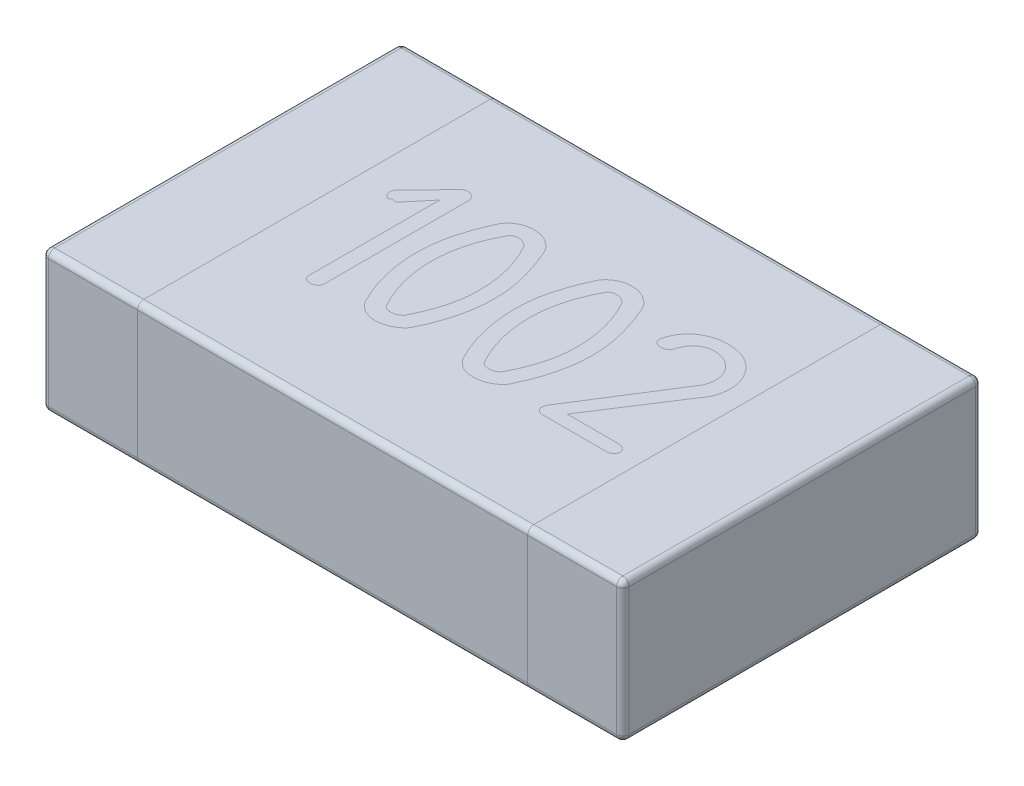
SolidWorks part; units mm, degrees
ref_plane "Front Plane" through (0, 0, 0) normal (0, 0, 1) x (1, 0, 0)
ref_plane "Top Plane" through (0, 0, 0) normal (0, 1, 0) x (1, 0, 0)
ref_plane "Right Plane" through (0, 0, 0) normal (1, 0, 0) x (0, 0, -1)
sketch "Sketch1" plane through (0, 0, 0) normal (0, 1, 0) x (1, 0, 0)
  line L1 (-0.91, -0.575) -> (0.91, -0.575)
  line L2 (-0.93, -0.555) -> (-0.93, 0.555)
  line L3 (-0.91, 0.575) -> (0.91, 0.575)
  line L4 (0.93, -0.555) -> (0.93, 0.555)
  line L5 (-0.93, -0.575) -> (0.93, 0.575) construction
  line L6 (-0.93, 0.575) -> (0.93, -0.575) construction
  arc A4 (-0.93, -0.555) -> (-0.91, -0.575) centre (-0.91, -0.555) ccw
  arc A5 (0.91, -0.575) -> (0.93, -0.555) centre (0.91, -0.555) ccw
  arc A6 (0.93, 0.555) -> (0.91, 0.575) centre (0.91, 0.555) ccw
  arc A7 (-0.91, 0.575) -> (-0.93, 0.555) centre (-0.91, 0.555) ccw
  point P0 (0, 0)
  dimension "D4" = 0.02
  dimension "D1" = 1.86
  dimension "D2" = 1.15
extrude "Boss-Extrude1" add sketch "Sketch1" along normal mid plane 0.45
sketch "Sketch3" plane through (0, 0.225, 0) normal (0, 1, 0) x (1, 0, 0)
  line L1 (-0.625, -0.575) -> (-0.625, 0.575)
  line L2 (0.625, -0.575) -> (0.625, 0.575)
  line L4 (0.91, 0.575) -> (-0.91, 0.575) construction
  point P4 (0, 0)
  point P8 (-0.625, 0)
  point P11 (0.625, 0)
  point P14 (0, 0)
  point P17 (0, -0.25)
  dimension "D1" = 1.25
sketch "Sketch4" plane through (0, 0, 0.575) normal (0, 0, 1) x (1, 0, 0)
  line L0 (-0.625, 0.225) -> (-0.625, -0.5946)
  line L1 (0.625, 0.225) -> (0.625, -0.5946)
sketch "Sketch5" plane through (0, 0, -0.575) normal (0, 0, -1) x (-1, 0, 0)
  line L0 (-0.625, 0.225) -> (-0.625, -0.5946) construction
  line L1 (-0.625, 0.225) -> (-0.625, -0.5946)
  line L2 (0.625, 0.225) -> (0.625, -0.5946) construction
  line L3 (0.625, 0.225) -> (0.625, -0.5946)
sketch "Sketch6" plane through (0, -0.225, 0) normal (0, -1, 0) x (1, 0, 0)
  line L0 (0.625, 0.575) -> (0.625, -0.575) construction
  line L1 (-0.625, 0.575) -> (-0.625, -0.575) construction
  line L2 (0.625, 0.575) -> (0.625, -0.575)
  line L3 (-0.625, 0.575) -> (-0.625, -0.575)
  line L4 (-0.91, 0.575) -> (0.91, 0.575) construction
  line L5 (0.91, -0.575) -> (-0.91, -0.575) construction
split line "Split Line2"
split line "Split Line3"
split line "Split Line4"
split line "Split Line5"
fillet "Fillet2" radius 0.02 24 edges at (0.7675, -0.225, 0.575) (-0.7675, -0.225, 0.575) (0, -0.225, 0.575) (-0.9241, -0.225, 0.5691) (-0.93, -0.225, 0) (-0.9241, -0.225, -0.5691) (-0.7675, -0.225, -0.575) (0.7675, -0.225, -0.575) (0, -0.225, -0.575) (0.9241, -0.225, -0.5691) (0.93, -0.225, 0) (0.9241, -0.225, 0.5691) (-0.7675, 0.225, -0.575) (0, 0.225, -0.575) (0.7675, 0.225, -0.575) (0.9241, 0.225, -0.5691) (0.93, 0.225, 0) (0.9241, 0.225, 0.5691) (-0.7675, 0.225, 0.575) (0, 0.225, 0.575) (0.7675, 0.225, 0.575) (-0.9241, 0.225, 0.5691) (-0.93, 0.225, 0) (-0.9241, 0.225, -0.5691)
ref_plane "Plane1" through (0, 1.225, 0) normal (0, 1, 0) x (1, 0, 0)
sketch "Sketch7" plane through (0, 1.225, 0) normal (0, 1, 0) x (1, 0, 0)
  line L0 (-0.7555, 0) -> (0.7555, 0) construction
  line L1 (-0.7555, -0.25) -> (0.7555, -0.25) construction
  text T0 "<b>1002</b>\r\n" font "SWIsop1" height 0.5
  point P4 (0, 0)
  point P8 (0, -0.25)
  dimension "D1" = 0.25
split line "Split Line6"
